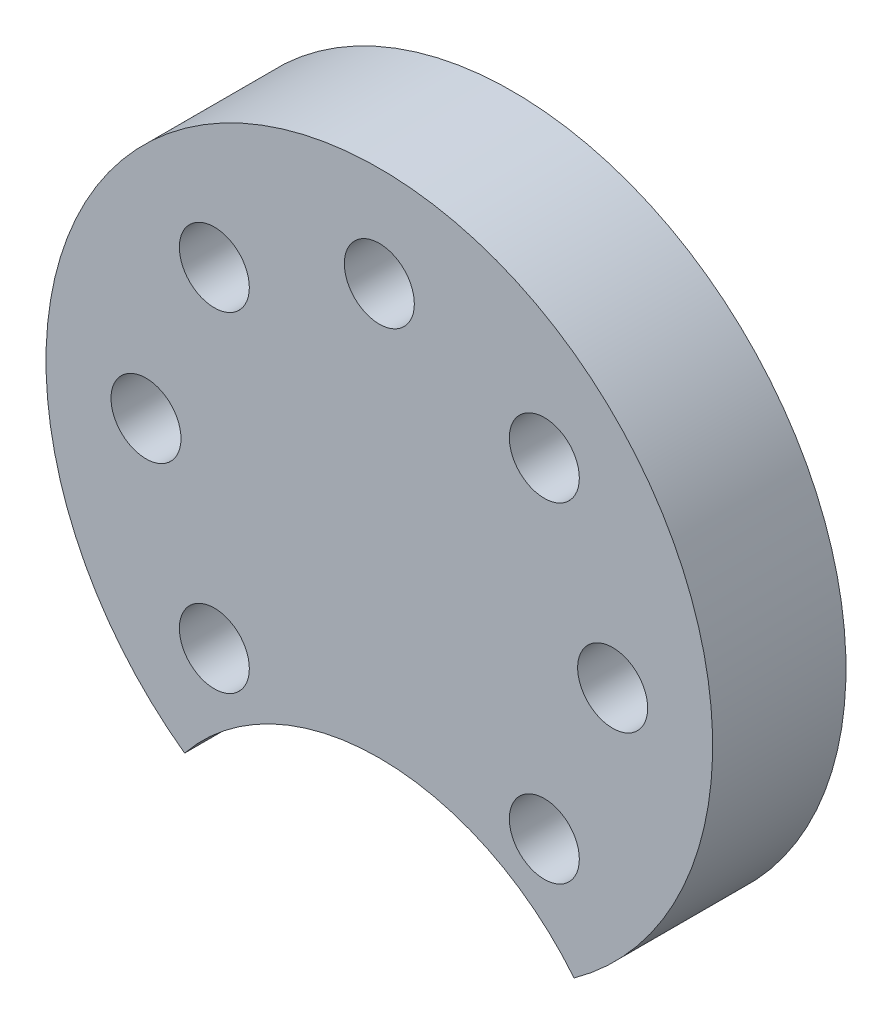
SolidWorks part; units mm, degrees
ref_plane "Front Plane" through (0, 0, 0) normal (0, 0, 1) x (1, 0, 0)
ref_plane "Top Plane" through (0, 0, 0) normal (0, 1, 0) x (1, 0, 0)
ref_plane "Right Plane" through (0, 0, 0) normal (1, 0, 0) x (0, 0, -1)
sketch "Sketch1" plane through (0, 0, 0) normal (0, 0, 1) x (1, 0, 0)
  line L0 (0, 4) -> (0, 6) construction
  line L1 (-4, 0) -> (-6, 0) construction
  line L2 (0, -4) -> (0, -6) construction
  line L3 (4, 0) -> (6, 0) construction
  line L4 (-6, 0) -> (-7, 0) construction
  line L5 (0, 6) -> (0, 7) construction
  line L6 (6, 0) -> (7, 0) construction
  line L7 (0, -6) -> (0, -7) construction
  circle A0 centre (0, 0) radius 10
  circle A2 centre (-7, 0) radius 1.05
  circle A3 centre (0, 7) radius 1.05
  circle A4 centre (0, -7) radius 1.05
  circle A5 centre (7, 0) radius 1.05
  circle A6 centre (4.9497, 4.9497) radius 1.05
  circle A7 centre (7, 0) radius 1.05
  circle A8 centre (4.9497, -4.9497) radius 1.05
  circle A9 centre (0, -7) radius 1.05
  circle A10 centre (-4.9497, -4.9497) radius 1.05
  circle A11 centre (-7, 0) radius 1.05
  circle A12 centre (-4.9497, 4.9497) radius 1.05
  circle A13 centre (0, 0) radius 4
  point P37 (0, 0)
  dimension "D1" = 20
  dimension "D2" = 8
  dimension "D11" = 2.1
  dimension "D12" = 2.1
  dimension "D13" = 2.1
  dimension "D14" = 2.1
  dimension "D3" = 2
  dimension "D4" = 2
  dimension "D5" = 2
  dimension "D6" = 2
  dimension "D7" = 1
  dimension "D8" = 1
  dimension "D9" = 1
  dimension "D10" = 1
  dimension "D15" = 8
extrude "Boss-Extrude1" add sketch "Sketch1" against normal blind 4 contours A0 A12 A10 A8 A6 A5 A4 A3 A2
sketch "Sketch2" plane through (0, 0, -4) normal (0, 0, -1) x (-1, 0, 0)
  line L0 (0, 4) -> (0, -20.32) construction
  circle A0 centre (0, -12.82) radius 7.5
  circle A2 centre (0, 0) radius 4 construction
  dimension "D1" = 15
  dimension "D2" = 24.32
extrude "Cut-Extrude1" cut sketch "Sketch2" against normal blind 10
sketch "Sketch3" plane through (0, 0, -4) normal (0, 0, -1) x (-1, 0, 0)
  circle A0 centre (0, 0) radius 4
  dimension "D1" = 8
extrude "Boss-Extrude2" add sketch "Sketch3" against normal blind 4
